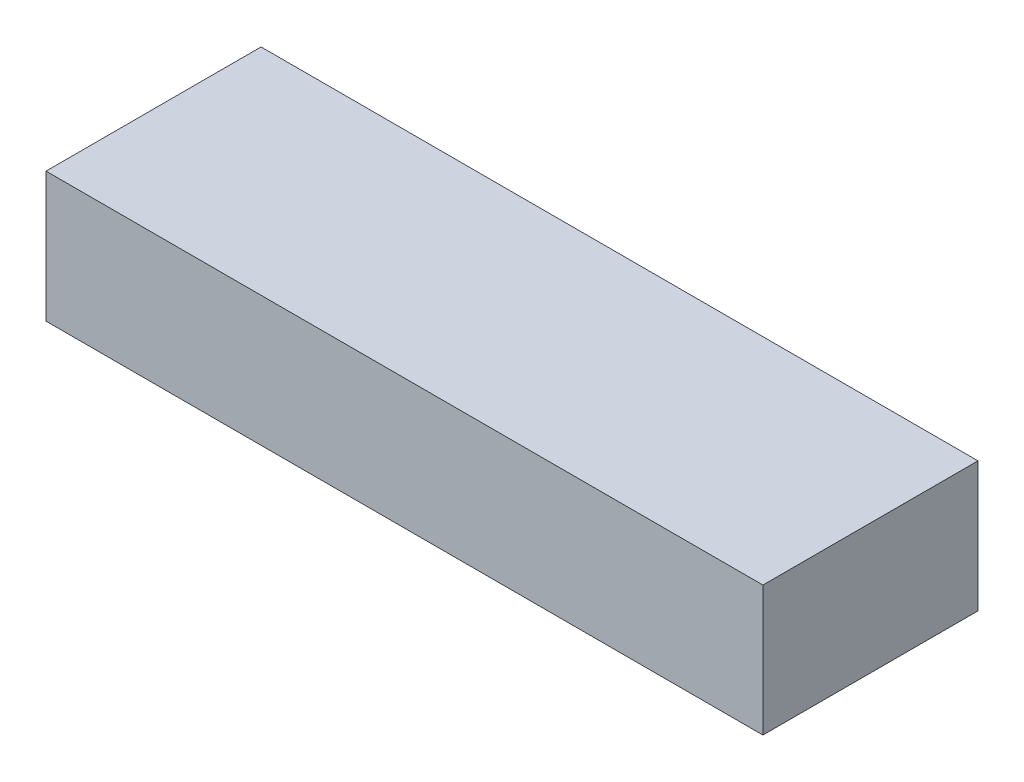
SolidWorks part; units mm, degrees
ref_plane "Ön Düzlem" through (0, 0, 0) normal (0, 0, 1) x (1, 0, 0)
ref_plane "Üst Düzlem" through (0, 0, 0) normal (0, 1, 0) x (1, 0, 0)
ref_plane "Sağ Düzlem" through (0, 0, 0) normal (1, 0, 0) x (0, 0, -1)
sketch "Çizim1" plane through (0, 0, 0) normal (0, 1, 0) x (1, 0, 0)
  line L1 (-80, -24) -> (80, -24)
  line L2 (-80, -24) -> (-80, 24)
  line L3 (-80, 24) -> (80, 24)
  line L4 (80, -24) -> (80, 24)
  line L5 (-80, -24) -> (80, 24) construction
  line L6 (-80, 24) -> (80, -24) construction
  point P0 (0, 0)
  dimension "D1" = 48
  dimension "D2" = 160
extrude "Yükseklik-Ekstrüzyon1" add sketch "Çizim1" along normal blind 29
